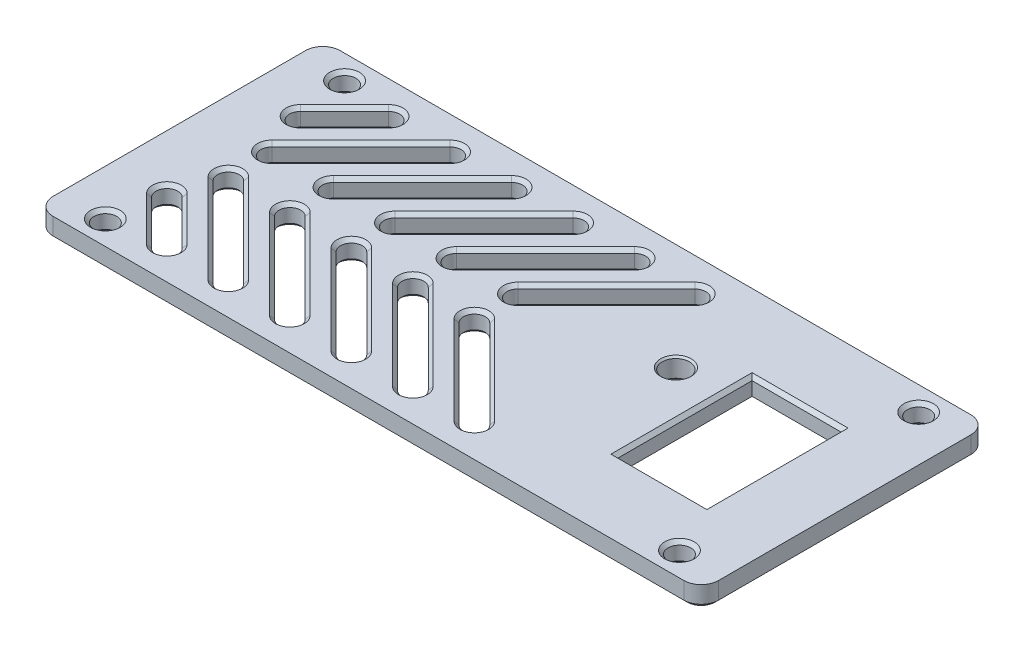
SolidWorks part; units mm, degrees
ref_plane "Plane XZ" through (0, 0, 0) normal (0, 0, 1) x (1, 0, 0)
ref_plane "Plane XY" through (0, 0, 0) normal (0, 1, 0) x (1, 0, 0)
ref_plane "Plane YZ" through (0, 0, 0) normal (1, 0, 0) x (0, 0, -1)
sketch "Sketch1" plane through (0, 0, 0) normal (0, 1, 0) x (1, 0, 0)
  line L0 (0, 20.955) -> (0, -20.955) construction
  line L1 (-48.5775, 20.955) -> (48.5775, 20.955)
  line L2 (-48.5775, 20.955) -> (-48.5775, -20.955)
  line L3 (-48.5775, -20.955) -> (48.5775, -20.955)
  line L4 (48.5775, 20.955) -> (48.5775, -20.955)
  dimension "D1" = 41.91
  dimension "D2" = 97.155
extrude "Boss-Extrude1" add sketch "Sketch1" along normal blind 3
fillet "Fillet1" radius 2.54 4 edges at (48.5775, 1.5, -20.955) (48.5775, 1.5, 20.955) (-48.5775, 1.5, 20.955) (-48.5775, 1.5, -20.955)
sketch "Sketch2" plane through (0, 3, 0) normal (0, 1, 0) x (1, 0, 0)
  line L0 (25.25, 0) -> (0, 0) construction
  line L1 (25.25, 9.8) -> (38.25, 9.8)
  line L2 (25.25, 9.8) -> (25.25, -9.8)
  line L3 (25.25, -9.8) -> (38.25, -9.8)
  line L4 (38.25, 9.8) -> (38.25, -9.8)
  line L5 (31.75, 9.8) -> (31.75, -9.8) construction
  dimension "D1" = 13
  dimension "D2" = 19.6
  dimension "D3" = 31.75
extrude "Cut-Extrude1" cut sketch "Sketch2" against normal through all
sketch "Sketch3" plane through (0, 3, 0) normal (0, 1, 0) x (1, 0, 0)
  line L0 (-41.91, 0) -> (41.91, 0) construction
  line L1 (-41.91, 17.4625) -> (41.91, 17.4625) construction
  line L2 (-41.91, 17.4625) -> (-41.91, -17.4625) construction
  line L3 (-41.91, -17.4625) -> (41.91, -17.4625) construction
  line L4 (41.91, 17.4625) -> (41.91, -17.4625) construction
  circle A0 centre (-41.91, 17.4625) radius 1.651
  circle A1 centre (-41.91, -17.4625) radius 1.651
  circle A2 centre (41.91, -17.4625) radius 1.651
  circle A3 centre (41.91, 17.4625) radius 1.651
  dimension "D3" = 3.302
  dimension "D1" = 83.82
  dimension "D2" = 34.925
extrude "Cut-Extrude2" cut sketch "Sketch3" against normal through all
ref_plane "Plane1" through (31.75, 0, 0) normal (-1, 0, 0) x (0, 0, 1)
sketch "Sketch4" plane through (0, 0, 0) normal (0, -1, 0) x (1, 0, 0)
  circle A0 centre (18.542, -5.3848) radius 1.9812
  dimension "D3" = 3.9624
  dimension "D1" = 5.3848
  dimension "D2" = 18.542
extrude "Cut-Extrude3" cut sketch "Sketch4" against normal blind 3.175
chamfer "Chamfer1" distance 0.254 angle 45 2 edges at (18.542, 0, -7.366) (18.542, 3, -3.4036)
sketch "Sketch5" plane through (0, 0, 0) normal (0, -1, 0) x (1, 0, 0)
  line L0 (-42.2275, 0) -> (42.2275, 0) construction
  line L1 (-42.2275, 17.78) -> (42.2275, 17.78) construction
  line L2 (-42.2275, 17.78) -> (-42.2275, -17.78) construction
  line L3 (-42.2275, -17.78) -> (42.2275, -17.78) construction
  line L4 (42.2275, 17.78) -> (42.2275, -17.78) construction
  line L5 (-79.8198, -27.1825) -> (2.735, 55.3723) construction
  line L13 (12.192, 20.955) -> (12.192, -20.955) construction
  line L14 (46.0375, -20.955) -> (-46.0375, -20.955) construction
  line L15 (-46.0375, 20.955) -> (46.0375, 20.955) construction
  line L16 (-42.2275, 1.5875) -> (12.192, 1.5875) construction
  line L17 (-42.2275, -1.5875) -> (12.192, -1.5875) construction
  line L18 (-41.91, 17.4625) -> (-38.5424, 14.0949) construction
  line L19 (-75.3296, -27.1825) -> (7.2251, 55.3723) construction
  line L20 (-70.8395, -27.1825) -> (11.7152, 55.3723) construction
  line L21 (-66.3494, -27.1825) -> (16.2053, 55.3723) construction
  line L22 (-61.8592, -27.1825) -> (20.6955, 55.3723) construction
  line L23 (-57.3691, -27.1825) -> (25.1856, 55.3723) construction
  line L24 (-52.879, -27.1825) -> (29.6757, 55.3723) construction
  line L25 (-48.3889, -27.1825) -> (34.1659, 55.3723) construction
  line L26 (-43.8987, -27.1825) -> (38.656, 55.3723) construction
  line L27 (-39.4086, -27.1825) -> (43.1461, 55.3723) construction
  line L28 (-34.9185, -27.1825) -> (47.6362, 55.3723) construction
  line L29 (-30.4284, -27.1825) -> (52.1264, 55.3723) construction
  line L30 (-25.9382, -27.1825) -> (56.6165, 55.3723) construction
  line L31 (-21.4481, -27.1825) -> (61.1066, 55.3723) construction
  line L32 (-16.958, -27.1825) -> (65.5967, 55.3723) construction
  line L33 (-12.4678, -27.1825) -> (70.0869, 55.3723) construction
  line L34 (-7.9777, -27.1825) -> (74.577, 55.3723) construction
  line L35 (-41.7625, 10.8748) -> (-35.3223, 17.315)
  line L36 (-39.5175, 8.6297) -> (-33.0772, 15.07)
  line L37 (-39.3595, 4.2975) -> (-26.342, 17.315)
  line L38 (-37.1145, 2.0525) -> (-24.097, 15.07)
  line L39 (-30.3793, 4.2975) -> (-17.3618, 17.315)
  line L40 (-28.1342, 2.0525) -> (-15.1167, 15.07)
  line L41 (-21.399, 4.2975) -> (-8.3815, 17.315)
  line L42 (-19.1539, 2.0525) -> (-6.1364, 15.07)
  line L43 (-12.4188, 4.2975) -> (0.5987, 17.315)
  line L44 (-10.1737, 2.0525) -> (2.8438, 15.07)
  line L45 (-3.4385, 4.2975) -> (9.482, 17.218)
  line L46 (-1.1934, 2.0525) -> (11.727, 14.9729)
  circle A0 centre (-41.91, 17.4625) radius 4.7625 construction
  circle A1 centre (-41.91, -17.4625) radius 4.7625 construction
  circle A2 centre (18.542, -5.3848) radius 2.2352 construction
  arc A3 (-41.7625, 10.8748) -> (-39.5175, 8.6297) centre (-40.64, 9.7522) ccw
  arc A4 (-35.3223, 17.315) -> (-33.0772, 15.07) centre (-34.1997, 16.1925) cw
  arc A5 (-26.342, 17.315) -> (-24.097, 15.07) centre (-25.2195, 16.1925) cw
  arc A6 (-39.3595, 4.2975) -> (-37.1145, 2.0525) centre (-38.237, 3.175) ccw
  arc A7 (-17.3618, 17.315) -> (-15.1167, 15.07) centre (-16.2392, 16.1925) cw
  arc A8 (-28.1342, 2.0525) -> (-30.3793, 4.2975) centre (-29.2567, 3.175) cw
  arc A9 (-8.3815, 17.315) -> (-6.1364, 15.07) centre (-7.259, 16.1925) cw
  arc A10 (-21.399, 4.2975) -> (-19.1539, 2.0525) centre (-20.2765, 3.175) ccw
  arc A11 (0.5987, 17.315) -> (2.8438, 15.07) centre (1.7213, 16.1925) cw
  arc A12 (-10.1737, 2.0525) -> (-12.4188, 4.2975) centre (-11.2962, 3.175) cw
  arc A13 (9.482, 17.218) -> (11.727, 14.9729) centre (10.6045, 16.0955) cw
  arc A14 (-3.4385, 4.2975) -> (-1.1934, 2.0525) centre (-2.316, 3.175) ccw
  dimension "D3" = 6.35
  dimension "D4" = 9.525
  dimension "D1" = 35.56
  dimension "D2" = 84.455
  dimension "D5" = 1.5875
  dimension "D6" = 1.5875
  dimension "D7" = 45
  dimension "D8" = 17
  dimension "D9" = 3.175
extrude "Cut-Extrude4" cut sketch "Sketch5" against normal through all
mirror "Mirror1" about plane through (0, 0, 0) normal (0, 0, 1) of "Cut-Extrude4"
chamfer "Chamfer2" distance 0.508 angle 45 8 edges at (31.75, 3, -9.8) (25.25, 3, 0) (38.25, 3, 0) (31.75, 3, 9.8) (31.75, 0, -9.8) (25.25, 0, 0) (38.25, 0, 0) (31.75, 0, 9.8)
chamfer "Chamfer3" distance 0.508 angle 45 96 edges at (-38.5424, 3, -14.0949) (-41.7625, 3, -8.6297) (-33.0772, 3, -17.315) (-36.2973, 3, -11.8498) (-32.8508, 3, -10.8063) (-39.3595, 3, -2.0525) (-24.097, 3, -17.315) (-30.6057, 3, -8.5612) (-23.8705, 3, -10.8063) (-30.3793, 3, -2.0525) (-15.1167, 3, -17.315) (-21.6254, 3, -8.5612) (-14.8903, 3, -10.8063) (-21.399, 3, -2.0525) (-6.1364, 3, -17.315) (-12.6452, 3, -8.5612) (-5.91, 3, -10.8063) (-12.4188, 3, -2.0525) (2.8438, 3, -17.315) (-3.6649, 3, -8.5612) (3.0217, 3, -10.7578) (-3.4385, 3, -2.0525) (11.727, 3, -17.218) (5.2668, 3, -8.5127) (-36.2973, 3, 11.8498) (-33.0772, 3, 17.315) (-41.7625, 3, 8.6297) (-38.5424, 3, 14.0949) (-30.6057, 3, 8.5612) (-24.097, 3, 17.315) (-39.3595, 3, 2.0525) (-32.8508, 3, 10.8063) (-21.6254, 3, 8.5612) (-15.1167, 3, 17.315) (-30.3793, 3, 2.0525) (-23.8705, 3, 10.8063) (-12.6452, 3, 8.5612) (-6.1364, 3, 17.315) (-21.399, 3, 2.0525) (-14.8903, 3, 10.8063) (-3.6649, 3, 8.5612) (2.8438, 3, 17.315) (-12.4188, 3, 2.0525) (-5.91, 3, 10.8063) (5.2668, 3, 8.5127) (11.727, 3, 17.218) (-3.4385, 3, 2.0525) (3.0217, 3, 10.7578) (3.0217, 0, 10.7578) (-3.4385, 0, 2.0525) (11.727, 0, 17.218) (5.2668, 0, 8.5127) (-5.91, 0, 10.8063) (-12.4188, 0, 2.0525) (2.8438, 0, 17.315) (-3.6649, 0, 8.5612) (-14.8903, 0, 10.8063) (-21.399, 0, 2.0525) (-6.1364, 0, 17.315) (-12.6452, 0, 8.5612) (-23.8705, 0, 10.8063) (-30.3793, 0, 2.0525) (-15.1167, 0, 17.315) (-21.6254, 0, 8.5612) (-32.8508, 0, 10.8063) (-39.3595, 0, 2.0525) (-24.097, 0, 17.315) (-30.6057, 0, 8.5612) (-38.5424, 0, 14.0949) (-41.7625, 0, 8.6297) (-33.0772, 0, 17.315) (-36.2973, 0, 11.8498) (-38.5424, 0, -14.0949) (-41.7625, 0, -8.6297) (-33.0772, 0, -17.315) (-36.2973, 0, -11.8498) (-32.8508, 0, -10.8063) (-39.3595, 0, -2.0525) (-24.097, 0, -17.315) (-30.6057, 0, -8.5612) (-23.8705, 0, -10.8063) (-30.3793, 0, -2.0525) (-15.1167, 0, -17.315) (-21.6254, 0, -8.5612) (-14.8903, 0, -10.8063) (-21.399, 0, -2.0525) (-6.1364, 0, -17.315) (-12.6452, 0, -8.5612) (-5.91, 0, -10.8063) (-12.4188, 0, -2.0525) (2.8438, 0, -17.315) (-3.6649, 0, -8.5612) (3.0217, 0, -10.7578) (-3.4385, 0, -2.0525) (11.727, 0, -17.218) (5.2668, 0, -8.5127)
chamfer "Chamfer4" distance 0.508 angle 45 8 edges at (-41.91, 0, 19.1135) (-41.91, 0, -15.8115) (41.91, 0, 19.1135) (41.91, 0, -15.8115) (41.91, 3, -15.8115) (41.91, 3, 19.1135) (-41.91, 3, -15.8115) (-41.91, 3, 19.1135)
chamfer "Chamfer5" distance 0.508 angle 45 8 edges at (0, 0, 20.955) (47.8336, 0, 20.2111) (-47.8336, 0, 20.2111) (48.5775, 0, 0) (-48.5775, 0, 0) (47.8336, 0, -20.2111) (-47.8336, 0, -20.2111) (0, 0, -20.955)
